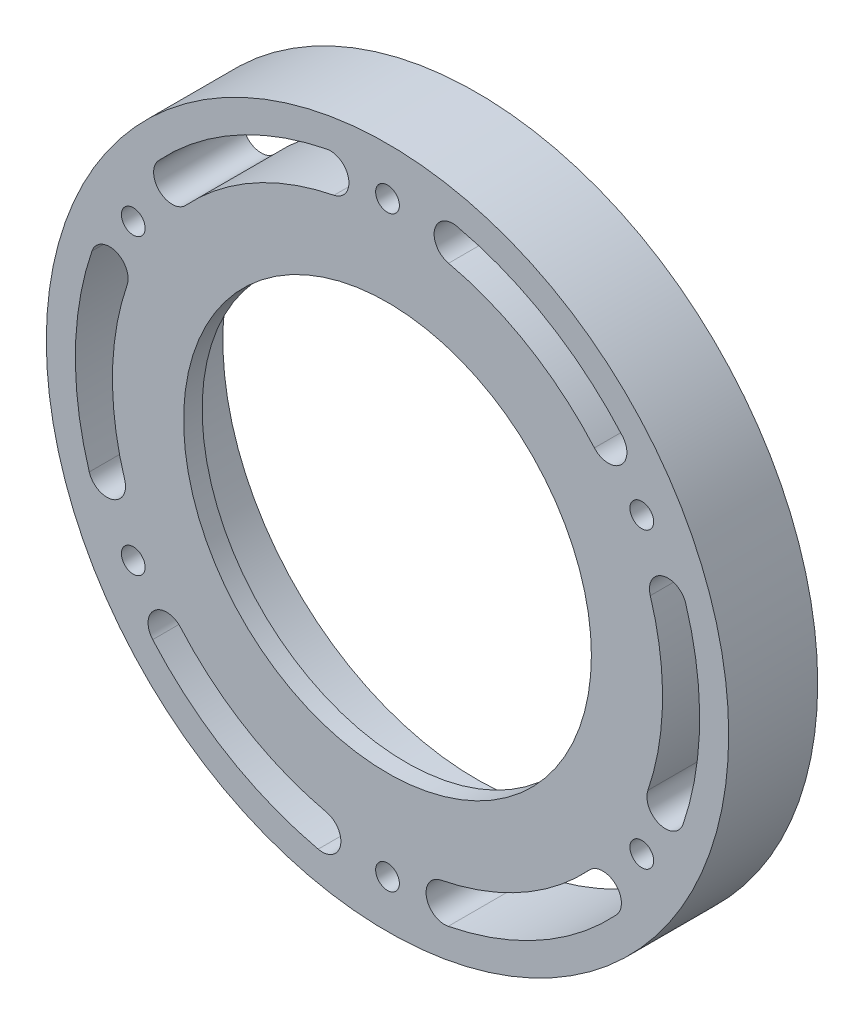
SolidWorks part; units mm, degrees
ref_plane "前视基准面" through (0, 0, 0) normal (0, 0, 1) x (1, 0, 0)
ref_plane "上视基准面" through (0, 0, 0) normal (0, 1, 0) x (1, 0, 0)
ref_plane "右视基准面" through (0, 0, 0) normal (1, 0, 0) x (0, 0, -1)
other "Configuration Table"
sketch "草图1" plane through (0, 0, 0) normal (0, 0, 1) x (1, 0, 0)
  line L0 (0, 72.4567) -> (0, -52.5061) construction
  circle A0 centre (0, 0) radius 34.2
  circle A1 centre (0, 0) radius 46
  circle A2 centre (0, 39.5831) radius 1.6
  circle A3 centre (34.2799, 19.7915) radius 1.6
  circle A4 centre (34.2799, -19.7915) radius 1.6
  circle A5 centre (0, -39.5831) radius 1.6
  circle A6 centre (-34.2799, -19.7915) radius 1.6
  circle A7 centre (-34.2799, 19.7915) radius 1.6
  arc A8 (-7.6993, 38.8271) -> (-29.0315, 26.9071) centre (0, 0) ccw construction
  arc A9 (-8.1855, 41.2793) -> (-30.865, 28.6065) centre (0, 0) ccw
  arc A10 (-7.213, 36.3748) -> (-27.1979, 25.2077) centre (0, 0) ccw
  arc A11 (-7.213, 36.3748) -> (-8.1855, 41.2793) centre (-7.6993, 38.8271) ccw
  arc A12 (-30.865, 28.6065) -> (-27.1979, 25.2077) centre (-29.0315, 26.9071) ccw
  arc A13 (29.7756, 26.0813) -> (8.7865, 38.5955) centre (0, 0) ccw construction
  arc A14 (31.6562, 27.7285) -> (9.3415, 41.0332) centre (0, 0) ccw
  arc A15 (27.895, 24.434) -> (8.2316, 36.1579) centre (0, 0) ccw
  arc A16 (27.895, 24.434) -> (31.6562, 27.7285) centre (29.7756, 26.0813) ccw
  arc A17 (9.3415, 41.0332) -> (8.2316, 36.1579) centre (8.7865, 38.5955) ccw
  arc A18 (37.4749, -12.7458) -> (37.818, 11.6884) centre (0, 0) ccw construction
  arc A19 (39.8417, -13.5508) -> (40.2065, 12.4266) centre (0, 0) ccw
  arc A20 (35.108, -11.9408) -> (35.4295, 10.9502) centre (0, 0) ccw
  arc A21 (35.108, -11.9408) -> (39.8417, -13.5508) centre (37.4749, -12.7458) ccw
  arc A22 (40.2065, 12.4266) -> (35.4295, 10.9502) centre (37.818, 11.6884) ccw
  arc A23 (7.6993, -38.8271) -> (29.0315, -26.9071) centre (0, 0) ccw construction
  arc A24 (8.1855, -41.2793) -> (30.865, -28.6065) centre (0, 0) ccw
  arc A25 (7.213, -36.3748) -> (27.1979, -25.2077) centre (0, 0) ccw
  arc A26 (7.213, -36.3748) -> (8.1855, -41.2793) centre (7.6993, -38.8271) ccw
  arc A27 (30.865, -28.6065) -> (27.1979, -25.2077) centre (29.0315, -26.9071) ccw
  arc A28 (-29.7756, -26.0813) -> (-8.7865, -38.5955) centre (0, 0) ccw construction
  arc A29 (-31.6562, -27.7285) -> (-9.3415, -41.0332) centre (0, 0) ccw
  arc A30 (-27.895, -24.434) -> (-8.2316, -36.1579) centre (0, 0) ccw
  arc A31 (-27.895, -24.434) -> (-31.6562, -27.7285) centre (-29.7756, -26.0813) ccw
  arc A32 (-9.3415, -41.0332) -> (-8.2316, -36.1579) centre (-8.7865, -38.5955) ccw
  arc A33 (-37.4749, 12.7458) -> (-37.818, -11.6884) centre (0, 0) ccw construction
  arc A34 (-39.8417, 13.5508) -> (-40.2065, -12.4266) centre (0, 0) ccw
  arc A35 (-35.108, 11.9408) -> (-35.4295, -10.9502) centre (0, 0) ccw
  arc A36 (-35.108, 11.9408) -> (-39.8417, 13.5508) centre (-37.4749, 12.7458) ccw
  arc A37 (-40.2065, -12.4266) -> (-35.4295, -10.9502) centre (-37.818, -11.6884) ccw
  circle A38 centre (0, 0) radius 39.5831 construction
  point P10 (-19.3082, 34.5545)
  point P21 (0, 0)
  point P28 (0, 0)
  point P31 (20.2709, 33.9987)
  point P38 (39.5792, -0.5558)
  point P45 (19.3082, -34.5545)
  point P52 (-20.2709, -33.9987)
  point P59 (-39.5792, 0.5558)
  point P64 (0, 0)
  point P65 (-18.4453, 32.078)
  point P66 (-18.0134, 32.3248)
  point P67 (-32.0469, 18.4931)
  point P68 (0, 0)
  point P69 (-39.5792, 0.5558)
  dimension "D1" = 92
  dimension "D2" = 68.4
  dimension "D3" = 6
  dimension "D4" = 6
extrude "凸台-拉伸1" add sketch "草图1" along normal blind 12
sketch "草图4" plane through (0, 0, 12) normal (0, 0, 1) x (1, 0, 0)
  circle A0 centre (0, 0) radius 34.2
  circle A1 centre (0, 0) radius 27.4883
extrude "凸台-拉伸2" add sketch "草图4" against normal blind 2.5
